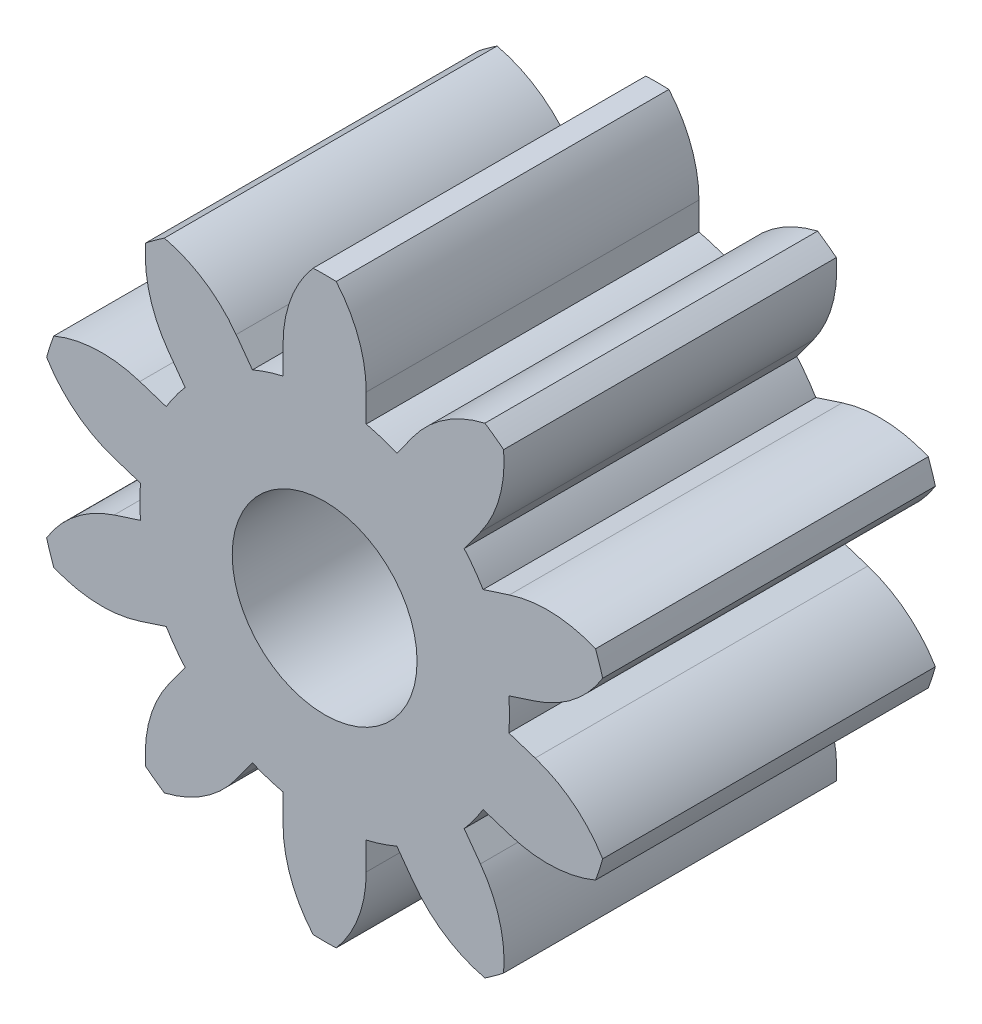
SolidWorks part; units mm, degrees
ref_plane "Plano frontal" through (0, 0, 0) normal (0, 0, 1) x (1, 0, 0)
ref_plane "Plano superior" through (0, 0, 0) normal (0, 1, 0) x (1, 0, 0)
ref_plane "Plano direito" through (0, 0, 0) normal (1, 0, 0) x (0, 0, -1)
sketch "Esboço1" plane through (0, 0, 0) normal (0, 0, 1) x (1, 0, 0)
  line L0 (0, 0) -> (0, -3.125) construction
  line L1 (-0.125, -3.1225) -> (0.125, -3.1225) construction
  line L2 (-0.45, -2.2487) -> (-0.45, -1.9487)
  line L3 (0.45, -2.2487) -> (0.45, -1.9487)
  line L4 (-1.6858, -1.5547) -> (-1.5095, -1.312)
  line L5 (-0.45, -2.2487) -> (0.45, -2.2487) construction
  line L6 (-0.9577, -2.0838) -> (-0.7814, -1.841)
  line L7 (-2.2777, -0.2669) -> (-1.9924, -0.1742)
  line L8 (-1.9996, -1.1229) -> (-1.7143, -1.0302)
  line L9 (-1.9996, 1.1229) -> (-1.7143, 1.0302)
  line L10 (-2.2777, 0.2669) -> (-1.9924, 0.1742)
  line L11 (-0.9577, 2.0838) -> (-0.7814, 1.841)
  line L12 (-1.6858, 1.5547) -> (-1.5095, 1.312)
  line L13 (0.45, 2.2487) -> (0.45, 1.9487)
  line L14 (-0.45, 2.2487) -> (-0.45, 1.9487)
  line L15 (1.6858, 1.5547) -> (1.5095, 1.312)
  line L16 (0.9577, 2.0838) -> (0.7814, 1.841)
  line L17 (2.2777, 0.2669) -> (1.9924, 0.1742)
  line L18 (1.9996, 1.1229) -> (1.7143, 1.0302)
  line L19 (1.9996, -1.1229) -> (1.7143, -1.0302)
  line L20 (2.2777, -0.2669) -> (1.9924, -0.1742)
  line L21 (0.9577, -2.0838) -> (0.7814, -1.841)
  line L22 (1.6858, -1.5547) -> (1.5095, -1.312)
  line L23 (-0.45, -1.9487) -> (0.45, -1.9487) construction
  circle A0 centre (0, 0) radius 3.125 construction
  circle A1 centre (0, 0) radius 2
  arc A2 (-0.125, -3.1225) -> (0.125, -3.1225) centre (0, 0) ccw
  circle A3 centre (0, 0) radius 2.2933 construction
  arc A4 (-0.45, -2.2487) -> (-0.125, -3.1225) centre (0.8871, -2.2487) ccw
  arc A5 (-1.6858, -1.5547) -> (-1.9365, -2.4527) centre (-0.6041, -2.3407) ccw
  arc A6 (0.125, -3.1225) -> (0.45, -2.2487) centre (-0.8871, -2.2487) ccw
  arc A7 (-1.9365, -2.4527) -> (-1.7342, -2.5996) centre (0, 0) ccw
  arc A8 (-1.7342, -2.5996) -> (-0.9577, -2.0838) centre (-2.0394, -1.2978) ccw
  arc A9 (-2.2777, -0.2669) -> (-3.0083, -0.846) centre (-1.8645, -1.5386) ccw
  arc A10 (-3.0083, -0.846) -> (-2.931, -1.0838) centre (0, 0) ccw
  arc A11 (-2.931, -1.0838) -> (-1.9996, -1.1229) centre (-2.4128, 0.1488) ccw
  arc A12 (-1.9996, 1.1229) -> (-2.931, 1.0838) centre (-2.4128, -0.1488) ccw
  arc A13 (-2.931, 1.0838) -> (-3.0083, 0.846) centre (0, 0) ccw
  arc A14 (-3.0083, 0.846) -> (-2.2777, 0.2669) centre (-1.8645, 1.5386) ccw
  arc A15 (-0.9577, 2.0838) -> (-1.7342, 2.5996) centre (-2.0394, 1.2978) ccw
  arc A16 (-1.7342, 2.5996) -> (-1.9365, 2.4527) centre (0, 0) ccw
  arc A17 (-1.9365, 2.4527) -> (-1.6858, 1.5547) centre (-0.6041, 2.3407) ccw
  arc A18 (0.45, 2.2487) -> (0.125, 3.1225) centre (-0.8871, 2.2487) ccw
  arc A19 (0.125, 3.1225) -> (-0.125, 3.1225) centre (0, 0) ccw
  arc A20 (-0.125, 3.1225) -> (-0.45, 2.2487) centre (0.8871, 2.2487) ccw
  arc A21 (1.6858, 1.5547) -> (1.9365, 2.4527) centre (0.6041, 2.3407) ccw
  arc A22 (1.9365, 2.4527) -> (1.7342, 2.5996) centre (0, 0) ccw
  arc A23 (1.7342, 2.5996) -> (0.9577, 2.0838) centre (2.0394, 1.2978) ccw
  arc A24 (2.2777, 0.2669) -> (3.0083, 0.846) centre (1.8645, 1.5386) ccw
  arc A25 (3.0083, 0.846) -> (2.931, 1.0838) centre (0, 0) ccw
  arc A26 (2.931, 1.0838) -> (1.9996, 1.1229) centre (2.4128, -0.1488) ccw
  arc A27 (1.9996, -1.1229) -> (2.931, -1.0838) centre (2.4128, 0.1488) ccw
  arc A28 (2.931, -1.0838) -> (3.0083, -0.846) centre (0, 0) ccw
  arc A29 (3.0083, -0.846) -> (2.2777, -0.2669) centre (1.8645, -1.5386) ccw
  arc A30 (0.9577, -2.0838) -> (1.7342, -2.5996) centre (2.0394, -1.2978) ccw
  arc A31 (1.7342, -2.5996) -> (1.9365, -2.4527) centre (0, 0) ccw
  arc A32 (1.9365, -2.4527) -> (1.6858, -1.5547) centre (0.6041, -2.3407) ccw
  point P89 (0, 0)
  dimension "D1" = 6.25
  dimension "D2" = 4
  dimension "D3" = 0.25
  dimension "D5" = 0.9
  dimension "D6" = 0.3
  dimension "D4" = 10
extrude "Ressalto-extrusão1" add sketch "Esboço1" along normal blind 3.6 contours A1 | A10 A11 L8 A1 L7 A9 | A13 A14 L10 A1 L9 A12 | A16 A17 L12 A1 L11 A15 | A19 A20 L14 A1 L13 A18 | A22 A23 L16 A1 L15 A21 | A25 A26 L18 A1 L17 A24 | A28 A29 L20 A1 L19 A27 | A31 A32 L22 A1 L21 A30 | A2 A6 L3 A1 L2 A4 | A7 A8 L6 A1 L4 A5
sketch "Esboço2" plane through (0, 0, 3.6) normal (0, 0, 1) x (1, 0, 0)
  circle A0 centre (0, 0) radius 1
  dimension "D1" = 2
extrude "Corte-extrusão1" cut sketch "Esboço2" against normal up to next
